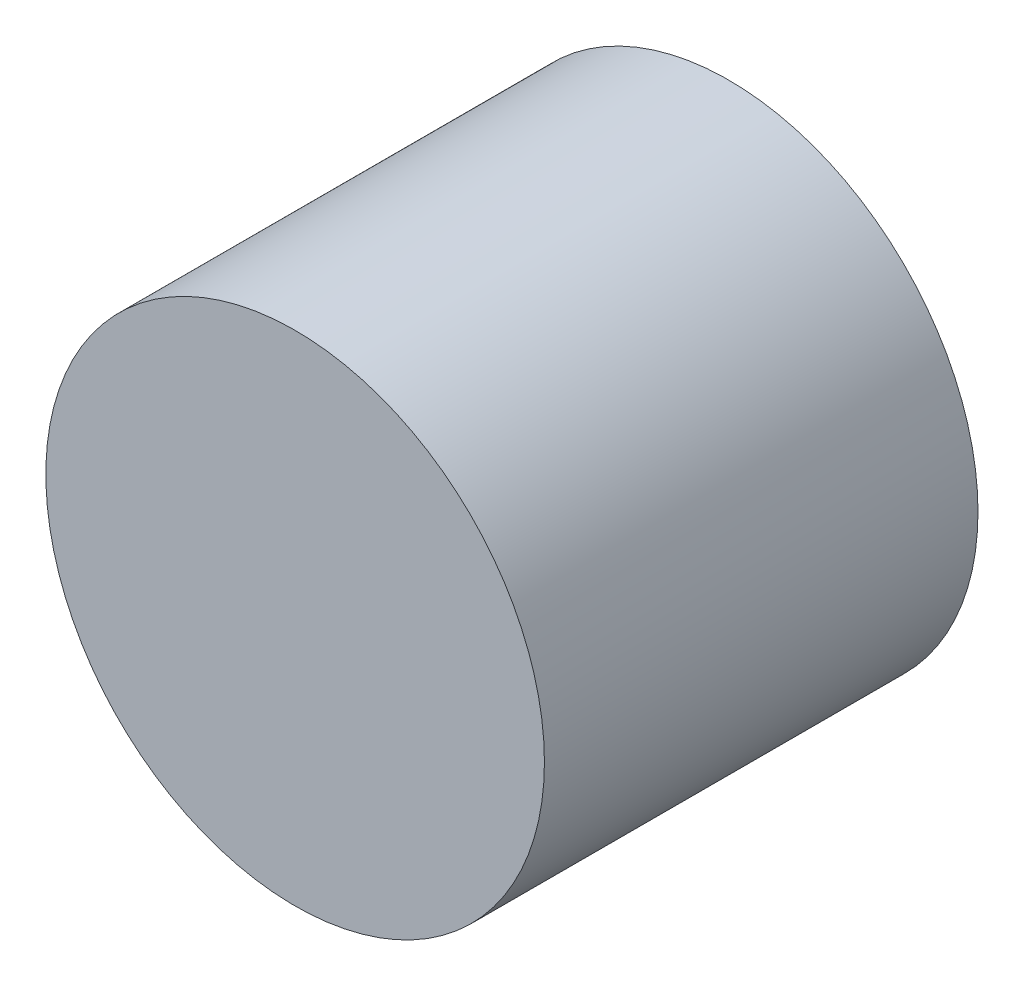
SolidWorks part; units mm, degrees
ref_plane "Alzado" through (0, 0, 0) normal (0, 0, 1) x (1, 0, 0)
ref_plane "Planta" through (0, 0, 0) normal (0, 1, 0) x (1, 0, 0)
ref_plane "Vista lateral" through (0, 0, 0) normal (1, 0, 0) x (0, 0, -1)
sketch "Croquis1" plane through (0, 0, 0) normal (0, 0, 1) x (1, 0, 0)
  circle A0 centre (0, 0) radius 5.75
  dimension "D1" = 11.5
extrude "Saliente-Extruir1" add sketch "Croquis1" along normal blind 10
